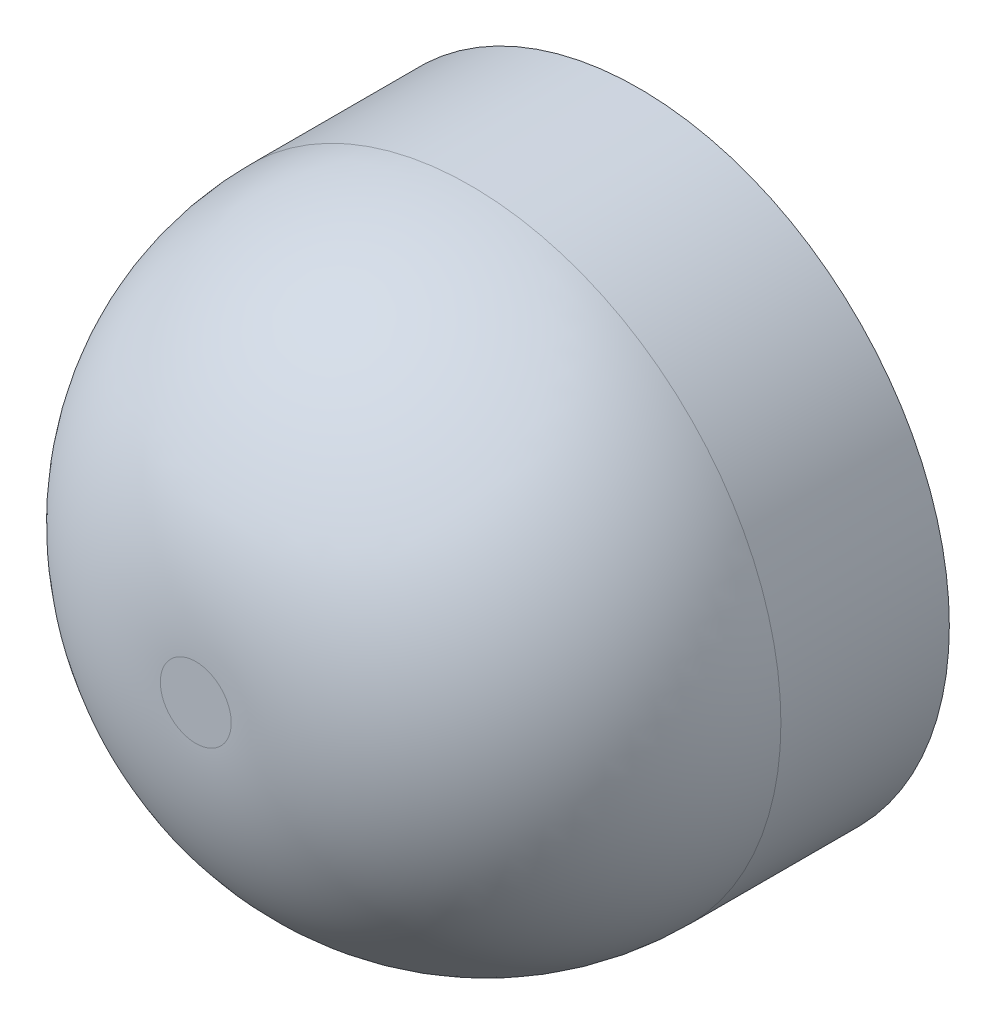
SolidWorks part; units mm, degrees
ref_plane "Alzado" through (0, 0, 0) normal (0, 0, 1) x (1, 0, 0)
ref_plane "Planta" through (0, 0, 0) normal (0, 1, 0) x (1, 0, 0)
ref_plane "Vista lateral" through (0, 0, 0) normal (1, 0, 0) x (0, 0, -1)
sketch "Croquis1" plane through (0, 0, 0) normal (0, 0, 1) x (1, 0, 0)
  circle A0 centre (0, 0) radius 3.5
  dimension "D1" = 7
extrude "Saliente-Extruir1" add sketch "Croquis1" along normal blind 5
fillet "Redondeo1" radius 3.1 1 edges at (3.5, 0, 5)
